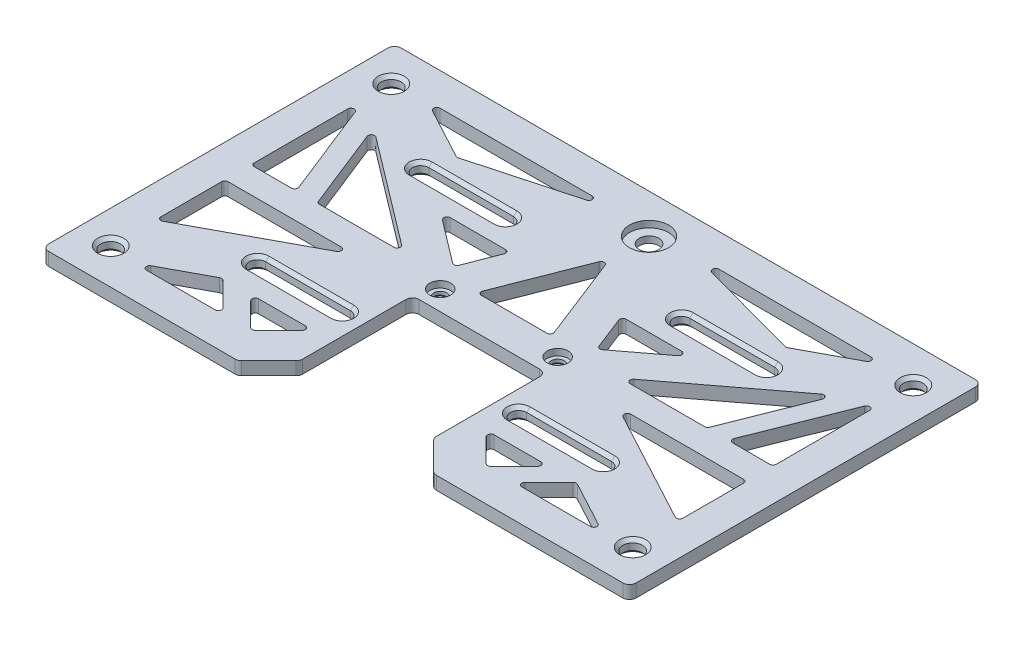
SolidWorks part; units mm, degrees
other "细节项目1"
ref_plane "前视基准面" through (0, 0, 0) normal (0, 0, 1) x (1, 0, 0)
ref_plane "上视基准面" through (0, 0, 0) normal (0, 1, 0) x (1, 0, 0)
ref_plane "右视基准面" through (0, 0, 0) normal (1, 0, 0) x (0, 0, -1)
other "Configuration Table"
sketch "草图1" plane through (0, 0, 0) normal (0, 1, 0) x (1, 0, 0)
  line L0 (0, 26.8995) -> (0, -26.8995) construction
  line L1 (-45, 26.8995) -> (45, 26.8995)
  line L2 (-45, 26.8995) -> (-45, -27.1005)
  line L3 (-45, -27.1005) -> (-15, -27.1005)
  line L4 (45, 26.8995) -> (45, -27.1005)
  line L5 (45, -0.1005) -> (-45, -0.1005) construction
  line L6 (-26.5, 12.3995) -> (-13.5, 12.3995) construction
  line L7 (-26.5, 13.6495) -> (-13.5, 13.6495)
  line L8 (-26.5, 11.1495) -> (-13.5, 11.1495)
  line L9 (-26.5, -12.6005) -> (-13.5, -12.6005) construction
  line L10 (-26.5, -11.3505) -> (-13.5, -11.3505)
  line L11 (-26.5, -13.8505) -> (-13.5, -13.8505)
  line L12 (-40, -21.6005) -> (40, -21.6005) construction
  line L13 (-40, 21.3995) -> (-40, -21.6005) construction
  line L14 (-40, 21.3995) -> (40, 21.3995) construction
  line L15 (40, 21.3995) -> (40, -21.6005) construction
  line L16 (-38.5, 21.3995) -> (-38.5, -21.6005) construction
  line L17 (38.5, -21.6005) -> (38.5, 21.3995) construction
  line L18 (40, 19.8995) -> (-40, 19.8995) construction
  line L19 (-40, -20.1005) -> (40, -20.1005) construction
  line L20 (-20, 12.3995) -> (-20, -12.6005) construction
  line L21 (13.5, 12.3995) -> (26.5, 12.3995) construction
  line L22 (13.5, 13.6495) -> (26.5, 13.6495)
  line L23 (13.5, 11.1495) -> (26.5, 11.1495)
  line L24 (13.5, -12.6005) -> (26.5, -12.6005) construction
  line L25 (13.5, -11.3505) -> (26.5, -11.3505)
  line L26 (13.5, -13.8505) -> (26.5, -13.8505)
  line L27 (20, 12.3995) -> (20, -12.6005) construction
  line L31 (-15, -27.1005) -> (-10.25, -22.3505)
  line L32 (10.25, -22.3505) -> (15, -27.1005)
  line L34 (0, -12.1005) -> (0, -26.8995) construction
  line L35 (15, -27.1005) -> (45, -27.1005)
  line L36 (-9, -2.1005) -> (9, -2.1005) construction
  line L39 (-10.25, -22.3505) -> (-10.25, -5.1005)
  line L40 (-10.25, -5.1005) -> (10.25, -5.1005)
  line L41 (10.25, -22.3505) -> (10.25, -5.1005)
  arc A0 (-26.5, 13.6495) -> (-26.5, 11.1495) centre (-26.5, 12.3995) ccw
  arc A1 (-13.5, 11.1495) -> (-13.5, 13.6495) centre (-13.5, 12.3995) ccw
  arc A2 (-26.5, -11.3505) -> (-26.5, -13.8505) centre (-26.5, -12.6005) ccw
  arc A3 (-13.5, -13.8505) -> (-13.5, -11.3505) centre (-13.5, -12.6005) ccw
  circle A4 centre (-40, 21.3995) radius 1.5
  circle A5 centre (-40, -21.6005) radius 1.5
  circle A6 centre (40, 21.3995) radius 1.5
  circle A7 centre (40, -21.6005) radius 1.5
  arc A8 (13.5, 13.6495) -> (13.5, 11.1495) centre (13.5, 12.3995) ccw
  arc A9 (26.5, 11.1495) -> (26.5, 13.6495) centre (26.5, 12.3995) ccw
  arc A10 (13.5, -11.3505) -> (13.5, -13.8505) centre (13.5, -12.6005) ccw
  arc A11 (26.5, -13.8505) -> (26.5, -11.3505) centre (26.5, -12.6005) ccw
  circle A12 centre (-9, -2.1005) radius 1
  circle A13 centre (9, -2.1005) radius 1
  circle A14 centre (0, 20.8995) radius 1.5
  point P8 (0, 0)
  point P12 (-20, 12.3995)
  point P17 (-27.75, 12.3995)
  point P18 (-12.25, 12.3995)
  point P21 (-20, -12.6005)
  point P36 (0, -21.6005)
  point P37 (-40, -0.1005)
  point P48 (-20, -0.1005)
  point P51 (20, 12.3995)
  point P60 (20, -12.6005)
  point P65 (0, -2.1005)
  point P69 (20, -0.1005)
  point P78 (0, 0)
  point P79 (0, 0)
  point P80 (0, 0)
  point P81 (0, -5.1005)
  dimension "D6" = 3
  dimension "D14" = 2
  dimension "D16" = 3.25
  dimension "D17" = 3
  dimension "D19" = 2
  dimension "D1" = 90
  dimension "D2" = 54
  dimension "D3" = 13
  dimension "D4" = 2.5
  dimension "D5" = 15.5
  dimension "D7" = 80
  dimension "D8" = 43
  dimension "D9" = 25
  dimension "D10" = 20
  dimension "D11" = 20
  dimension "D12" = 25
  dimension "D13" = 15
  dimension "D15" = 18
  dimension "D18" = 23
  dimension "D20" = 2
  dimension "D21" = 25
  dimension "D22" = 3
extrude "凸台-拉伸1" add sketch "草图1" along normal blind 2
sketch "草图3" plane through (0, 2, 0) normal (0, 1, 0) x (1, 0, 0)
  circle A0 centre (-9, -2.1005) radius 1.6
  circle A1 centre (9, -2.1005) radius 1.6
  circle A2 centre (0, 20.8995) radius 3
  circle A3 centre (0, 20.8995) radius 3
  point P4 (9, -2.1005)
  point P5 (-9, -2.1005)
  point P6 (0, 0)
  point P7 (0, 0)
  dimension "D2" = 3.2
  dimension "D3" = 3.2
  dimension "D1" = 1.5
extrude "切除-拉伸2" cut sketch "草图3" against normal blind 1 contours A3 | A0 | A1
sketch "草图2" plane through (0, 2, 0) normal (0, 1, 0) x (1, 0, 0)
  line L8 (-45, 26.8995) -> (-45, -27.1005) construction
  line L15 (-10.25, -22.3505) -> (-10.25, -5.1005) construction
  line L16 (45, 26.8995) -> (-45, 26.8995) construction
  line L17 (45, -27.1005) -> (45, 26.8995) construction
  line L18 (-45, -27.1005) -> (-15, -27.1005) construction
  line L19 (-36, -22.1005) -> (-22.2867, -22.1005)
  line L33 (-22.2867, -22.1005) -> (-27.0808, -17.3064)
  line L40 (-27.0808, -17.3064) -> (-36, -22.1005)
  line L47 (-18.0441, -22.1005) -> (-22.8382, -17.3064)
  line L53 (-22.8382, -17.3064) -> (-13.25, -17.3064)
  line L60 (-13.25, -17.3064) -> (-18.0441, -22.1005)
  line L61 (-45, -0.1005) -> (45, -0.1005) construction
  line L62 (-40, -14.7479) -> (-20.1909, -4.1005)
  line L63 (-20.1909, -4.1005) -> (-40, -4.1005)
  line L64 (-40, -4.1005) -> (-40, -14.7479)
  line L68 (0, 14.8995) -> (-5.7434, 0.2221)
  line L69 (-5.7434, 0.2221) -> (5.7434, 0.2221)
  line L70 (5.7434, 0.2221) -> (0, 14.8995)
  line L71 (0, 14.8995) -> (0, 0.2221) construction
  line L73 (-15, -27.1005) -> (-10.25, -22.3505) construction
  line L74 (-40, -21.6005) -> (40, 21.3995) construction
  line L75 (-40, 21.3995) -> (40, -21.6005) construction
  line L79 (-35, 21.8995) -> (-6, 21.8995)
  line L80 (-6, 21.8995) -> (-25.2326, 16.6495)
  line L81 (-25.2326, 16.6495) -> (-35, 21.8995)
  line L85 (-13.5, 13.6495) -> (-26.5, 13.6495) construction
  line L86 (0, 20.8995) -> (-9, -2.1005) construction
  line L87 (-45, -2.1005) -> (-9, -2.1005) construction
  line L88 (9, -2.1005) -> (0, 20.8995) construction
  line L89 (0, 20.8995) -> (0, -12.6005) construction
  line L96 (-29.8493, -0.1005) -> (-35.5436, 14.2406)
  line L97 (-35.5436, 14.2406) -> (-16.6256, -0.1005)
  line L98 (-16.6256, -0.1005) -> (-29.8493, -0.1005)
  line L99 (-40, 21.3995) -> (-26.5, -12.6005) construction
  line L100 (-13.5, -12.6005) -> (-9, -2.1005) construction
  line L101 (26.5, -12.6005) -> (40, 21.3995) construction
  line L102 (13.5, -12.6005) -> (9, -2.1005) construction
  line L103 (-9, -2.1005) -> (9, -2.1005) construction
  line L104 (9, -2.1005) -> (45, -2.1005) construction
  line L105 (-40, 17.3349) -> (-40, -0.1005)
  line L106 (-40, -0.1005) -> (-33.0772, -0.1005)
  line L107 (-33.0772, -0.1005) -> (-40, 17.3349)
  line L108 (-40, 21.3995) -> (-9, -2.1005) construction
  line L109 (9, -2.1005) -> (40, 21.3995) construction
  line L110 (-19.2106, 8.1495) -> (-8.5203, 8.1495)
  line L111 (-8.5203, 8.1495) -> (-10.9659, 1.8995)
  line L112 (-10.9659, 1.8995) -> (-19.2106, 8.1495)
  line L113 (-26.5, 11.1495) -> (-13.5, 11.1495) construction
  line L114 (0, 20.8995) -> (-13.5, 12.3995) construction
  line L115 (-13.5, -12.6005) -> (13.5, -12.6005) construction
  line L119 (22.8382, -17.3064) -> (13.25, -17.3064)
  line L120 (18.0441, -22.1005) -> (22.8382, -17.3064)
  line L121 (13.25, -17.3064) -> (18.0441, -22.1005)
  line L122 (22.2867, -22.1005) -> (27.0808, -17.3064)
  line L123 (36, -22.1005) -> (22.2867, -22.1005)
  line L124 (27.0808, -17.3064) -> (36, -22.1005)
  line L125 (20.1909, -4.1005) -> (40, -4.1005)
  line L126 (40, -14.7479) -> (20.1909, -4.1005)
  line L127 (40, -4.1005) -> (40, -14.7479)
  line L128 (8.5203, 8.1495) -> (10.9659, 1.8995)
  line L129 (19.2106, 8.1495) -> (8.5203, 8.1495)
  line L130 (10.9659, 1.8995) -> (19.2106, 8.1495)
  line L131 (35.5436, 14.2406) -> (16.6256, -0.1005)
  line L132 (29.8493, -0.1005) -> (35.5436, 14.2406)
  line L133 (16.6256, -0.1005) -> (29.8493, -0.1005)
  line L134 (40, -0.1005) -> (33.0772, -0.1005)
  line L135 (40, 17.3349) -> (40, -0.1005)
  line L136 (33.0772, -0.1005) -> (40, 17.3349)
  line L137 (6, 21.8995) -> (25.2326, 16.6495)
  line L138 (35, 21.8995) -> (6, 21.8995)
  line L139 (25.2326, 16.6495) -> (35, 21.8995)
  circle A0 centre (0, 20.8995) radius 3 construction
  circle A1 centre (9, -2.1005) radius 1 construction
  arc A3 (-26.5, -11.3505) -> (-26.5, -13.8505) centre (-26.5, -12.6005) ccw construction
  circle A5 centre (-40, 21.3995) radius 1.5 construction
  circle A6 centre (-9, -2.1005) radius 1 construction
  point P35 (0, 0)
  point P36 (0, 0)
  point P45 (0, 0)
  point P46 (0, -12.6005)
  point P47 (0, 0)
  point P49 (0, 0)
  point P50 (0, 0)
  point P51 (0, 0)
  dimension "D4" = 4
  dimension "D12" = 4.5
  dimension "D10" = 5
  dimension "D1" = 6
  dimension "D3" = 5
  dimension "D5" = 6
  dimension "D6" = 3
  dimension "D7" = 4
  dimension "D8" = 3
  dimension "D9" = 5
  dimension "D11" = 5
  dimension "D13" = 3
  dimension "D14" = 2
  dimension "D18" = 5
  dimension "D19" = 3
  dimension "D20" = 2
  dimension "D21" = 5
  dimension "D22" = 4
  dimension "D23" = 2
  dimension "D24" = 1.5
  dimension "D25" = 1.5
  dimension "D26" = 2
  dimension "D27" = 3
extrude "切除-拉伸3" cut sketch "草图2" against normal blind 2
fillet "圆角3" radius 1 10 edges at (45, 1, -26.8995) (-45, 1, -26.8995) (-45, 1, 27.1005) (45, 1, 27.1005) (15, 1, 27.1005) (-15, 1, 27.1005) (10.25, 1, 5.1005) (10.25, 1, 22.3505) (-10.25, 1, 5.1005) (-10.25, 1, 22.3505)
chamfer "倒角2" distance 0.5 angle 45 42 edges at (-20, 0, -13.6495) (-27.75, 0, -12.3995) (-20, 0, -11.1495) (-12.25, 0, -12.3995) (20, 0, -13.6495) (12.25, 0, -12.3995) (20, 0, -11.1495) (27.75, 0, -12.3995) (20, 0, 11.3505) (12.25, 0, 12.6005) (20, 0, 13.8505) (27.75, 0, 12.6005) (-20, 0, 11.3505) (-27.75, 0, 12.6005) (-20, 0, 13.8505) (-12.25, 0, 12.6005) (-27.75, 2, 12.6005) (-20, 2, 13.8505) (-12.25, 2, 12.6005) (-20, 2, 11.3505) (12.25, 2, 12.6005) (20, 2, 13.8505) (27.75, 2, 12.6005) (20, 2, 11.3505) (12.25, 2, -12.3995) (20, 2, -11.1495) (27.75, 2, -12.3995) (20, 2, -13.6495) (-20, 2, -11.1495) (-27.75, 2, -12.3995) (-20, 2, -13.6495) (-12.25, 2, -12.3995) (40, 2, 23.1005) (40, 0, 23.1005) (-40, 2, 23.1005) (-40, 0, 23.1005) (-9, 0, 3.1005) (9, 0, 3.1005) (40, 2, -19.8995) (40, 0, -19.8995) (-40, 2, -19.8995) (-40, 0, -19.8995)
fillet "圆角4" radius 0.5 45 edges at (6, 1, -21.8995) (-6, 1, -21.8995) (-40, 1, -17.3349) (-33.0772, 1, 0.1005) (-16.6256, 1, 0.1005) (36, 1, 22.1005) (-22.2867, 1, 22.1005) (-40, 1, 14.7479) (10.9659, 1, -1.8995) (5.7434, 1, -0.2221) (40, 1, 0.1005) (29.8493, 1, 0.1005) (25.2326, 1, -16.6495) (-25.2326, 1, -16.6495) (-10.9659, 1, -1.8995) (-18.0441, 1, 22.1005) (18.0441, 1, 22.1005) (40, 1, 14.7479) (35.5436, 1, -14.2406) (40, 1, -17.3349) (-35.5436, 1, -14.2406) (13.25, 1, 17.3064) (-22.8382, 1, 17.3064) (8.5203, 1, -8.1495) (-19.2106, 1, -8.1495) (-35, 1, -21.8995) (20.1909, 1, 4.1005) (-40, 1, 4.1005) (-20.1909, 1, 4.1005) (40, 1, 4.1005) (-8.5203, 1, -8.1495) (35, 1, -21.8995) (19.2106, 1, -8.1495) (-13.25, 1, 17.3064) (22.8382, 1, 17.3064) (-27.0808, 1, 17.3064) (27.0808, 1, 17.3064) (0, 1, -14.8995) (-40, 1, 0.1005) (33.0772, 1, 0.1005) (-5.7434, 1, -0.2221) (-29.8493, 1, 0.1005) (16.6256, 1, 0.1005) (22.2867, 1, 22.1005) (-36, 1, 22.1005)
